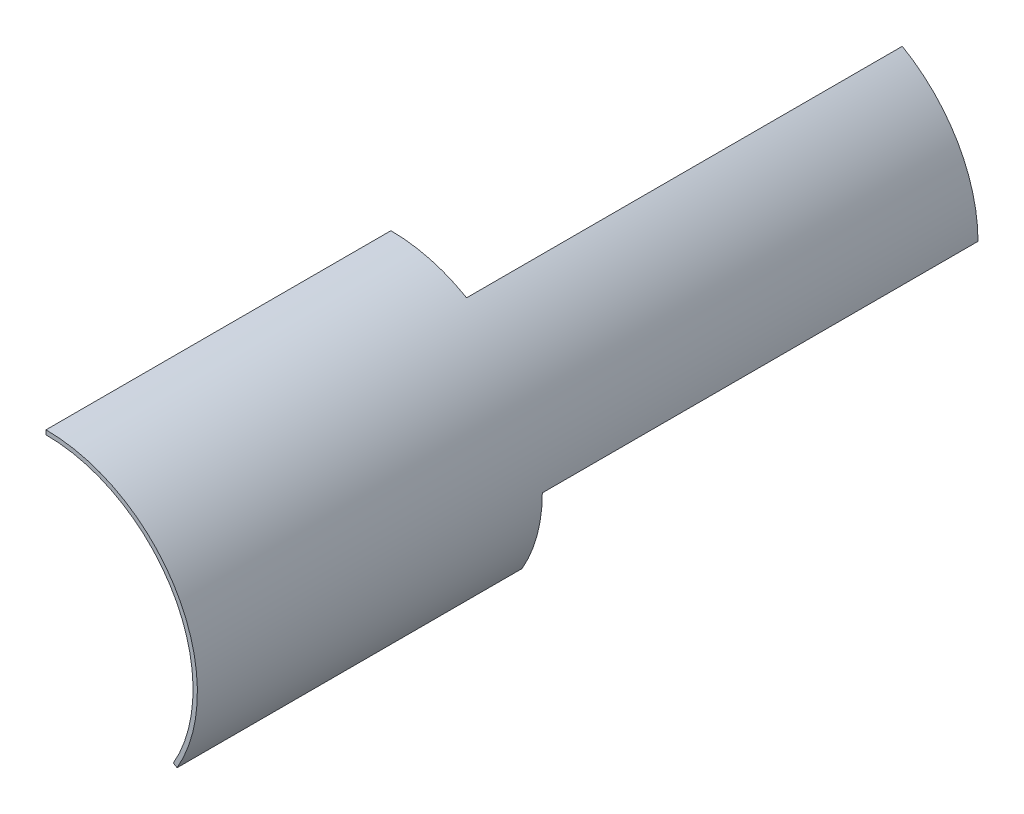
SolidWorks part; units mm, degrees
ref_plane "Front" through (0, 0, 0) normal (0, 0, 1) x (1, 0, 0)
ref_plane "Top" through (0, 0, 0) normal (0, 1, 0) x (1, 0, 0)
ref_plane "Right" through (0, 0, 0) normal (1, 0, 0) x (0, 0, -1)
sketch "Эскиз1" plane through (0, 0, 0) normal (1, 0, 0) x (0, 0, -1)
  line L0 (0, 41.7) -> (0, 40.5)
  line L1 (0, 40.5) -> (95, 40.5)
  line L2 (95, 40.5) -> (95, 41.7)
  line L3 (95, 41.7) -> (0, 41.7)
  line L4 (0, 0) -> (40.5832, 0) construction
  dimension "D1" = 1.2
  dimension "D2" = 40.5
  dimension "D3" = 95
revolve "Повернуть1" add sketch "Эскиз1" angle 120 about L4
ref_axis "Ось1" through (0, 0, -95) along (0, 0, 1)
ref_plane "Плоскость1" through (0, 0, 0) normal (0.5, -0.866, 0) x (0, 0, 1)
sketch "Эскиз3" plane through (0, 0, 0) normal (0.5, -0.866, 0) x (0, 0, 1)
  line L0 (-95, -40.5) -> (-215, -40.5)
  line L1 (-95, -20.85) -> (-95, -41.7) construction
  line L2 (-215, -40.5) -> (-215, -41.7)
  line L3 (-215, -41.7) -> (-95, -41.7)
  line L4 (-95, -41.7) -> (-95, -40.5)
  dimension "D1" = 1.2
  dimension "D2" = 40.5
  dimension "D3" = 120
revolve "Повернуть2" add sketch "Эскиз3" angle 30 about axis through (0, 0, -95) along (0, 0, 1) other way angle 30
